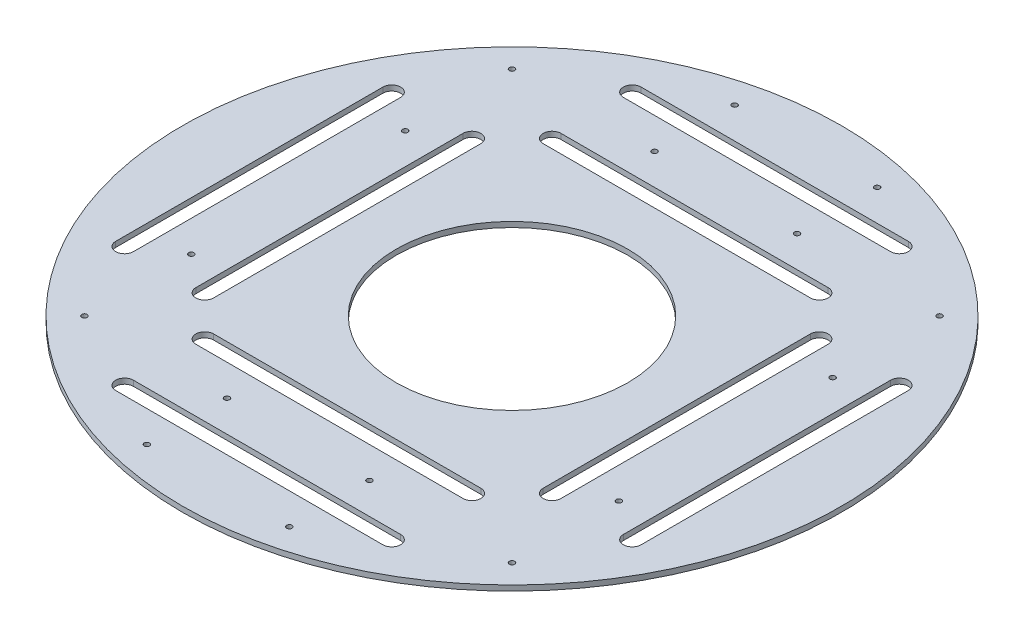
SolidWorks part; units mm, degrees
ref_plane "前视基准面" through (0, 0, 0) normal (0, 0, 1) x (1, 0, 0)
ref_plane "上视基准面" through (0, 0, 0) normal (0, 1, 0) x (1, 0, 0)
ref_plane "右视基准面" through (0, 0, 0) normal (1, 0, 0) x (0, 0, -1)
sketch "草图1" plane through (0, 0, 0) normal (0, 1, 0) x (1, 0, 0)
  line L0 (-364.0243, 0) -> (364.0243, 0) construction
  line L1 (0, -262.0813) -> (0, 262.0813) construction
  line L2 (-75, 97.5) -> (75, 97.5) construction
  line L4 (-142.5, -75) -> (-142.5, 75) construction
  line L5 (-137.5, -75) -> (-137.5, 75)
  line L6 (-147.5, -75) -> (-147.5, 75)
  line L7 (-75, -97.5) -> (75, -97.5) construction
  line L8 (-97.5, -75) -> (-97.5, 75) construction
  line L9 (-102.5, -75) -> (-102.5, 75)
  line L10 (-75, -102.5) -> (75, -102.5)
  line L11 (-75, -92.5) -> (75, -92.5)
  line L12 (-75, -142.5) -> (75, -142.5) construction
  line L13 (-75, -137.5) -> (75, -137.5)
  line L14 (-92.5, -75) -> (-92.5, 75)
  line L15 (-75, -147.5) -> (75, -147.5)
  line L16 (142.5, -75) -> (142.5, 75) construction
  line L17 (137.5, -75) -> (137.5, 75)
  line L18 (147.5, -75) -> (147.5, 75)
  line L19 (97.5, -75) -> (97.5, 75) construction
  line L20 (102.5, -75) -> (102.5, 75)
  line L21 (92.5, -75) -> (92.5, 75)
  line L22 (-75, 102.5) -> (75, 102.5)
  line L23 (-75, 142.5) -> (75, 142.5) construction
  line L24 (-75, 137.5) -> (75, 137.5)
  line L25 (-75, 147.5) -> (75, 147.5)
  line L26 (-75, 92.5) -> (75, 92.5)
  circle A0 centre (0, 0) radius 185
  circle A1 centre (120, 120) radius 1.5
  circle A2 centre (-120, 120) radius 1.5
  circle A3 centre (-120, -120) radius 1.5
  circle A4 centre (120, -120) radius 1.5
  circle A5 centre (0, 0) radius 65
  arc A6 (-102.5, -75) -> (-92.5, -75) centre (-97.5, -75) ccw
  arc A7 (-92.5, 75) -> (-102.5, 75) centre (-97.5, 75) ccw
  arc A8 (-137.5, -75) -> (-147.5, -75) centre (-142.5, -75) cw
  arc A9 (-147.5, 75) -> (-137.5, 75) centre (-142.5, 75) cw
  arc A10 (-75, -102.5) -> (-75, -92.5) centre (-75, -97.5) cw
  arc A11 (75, -92.5) -> (75, -102.5) centre (75, -97.5) cw
  arc A12 (-75, -137.5) -> (-75, -147.5) centre (-75, -142.5) ccw
  arc A13 (75, -147.5) -> (75, -137.5) centre (75, -142.5) ccw
  arc A14 (137.5, -75) -> (147.5, -75) centre (142.5, -75) ccw
  arc A15 (147.5, 75) -> (137.5, 75) centre (142.5, 75) ccw
  arc A16 (102.5, -75) -> (92.5, -75) centre (97.5, -75) cw
  arc A17 (92.5, 75) -> (102.5, 75) centre (97.5, 75) cw
  arc A18 (-75, 137.5) -> (-75, 147.5) centre (-75, 142.5) cw
  arc A19 (75, 147.5) -> (75, 137.5) centre (75, 142.5) cw
  arc A20 (-75, 102.5) -> (-75, 92.5) centre (-75, 97.5) ccw
  arc A21 (75, 92.5) -> (75, 102.5) centre (75, 97.5) ccw
  circle A22 centre (40, 165) radius 1.5
  circle A23 centre (40, 120) radius 1.5
  circle A24 centre (-40, 120) radius 1.5
  circle A25 centre (-40, 165) radius 1.5
  circle A26 centre (-40, -165) radius 1.5
  circle A27 centre (-40, -120) radius 1.5
  circle A28 centre (40, -120) radius 1.5
  circle A29 centre (40, -165) radius 1.5
  circle A30 centre (120, 60) radius 1.5
  circle A31 centre (120, -60) radius 1.5
  circle A32 centre (-120, -60) radius 1.5
  circle A33 centre (-120, 60) radius 1.5
  point P14 (0, 0)
  point P17 (0, 0)
  point P21 (-142.5, 0)
  point P24 (-120, 120)
  point P25 (120, 120)
  point P26 (-120, 120)
  point P27 (120, 120)
  point P28 (-120, 120)
  point P34 (-97.5, 0)
  point P40 (0, -97.5)
  point P47 (0, -142.5)
  point P54 (142.5, 0)
  point P61 (97.5, 0)
  point P67 (0, 97.5)
  point P70 (0, 142.5)
  point P79 (0, 142.5)
  point P83 (0, 120)
  point P88 (0, 165)
  point P102 (120, 0)
  point P111 (0, 0)
  point P115 (0, 0)
  dimension "D1" = 130
  dimension "D2" = 3
  dimension "D3" = 60
  dimension "D5" = 97.5
  dimension "D4" = 75
  dimension "D6" = 120
  dimension "D7" = 142.5
  dimension "D11" = 5
  dimension "D12" = 370
  dimension "D8" = 165
  dimension "D9" = 120
  dimension "D10" = 40
extrude "凸台-拉伸1" add sketch "草图1" along normal blind 3
sketch "草图2" plane through (0, 3, 0) normal (0, 1, 0) x (1, 0, 0)
